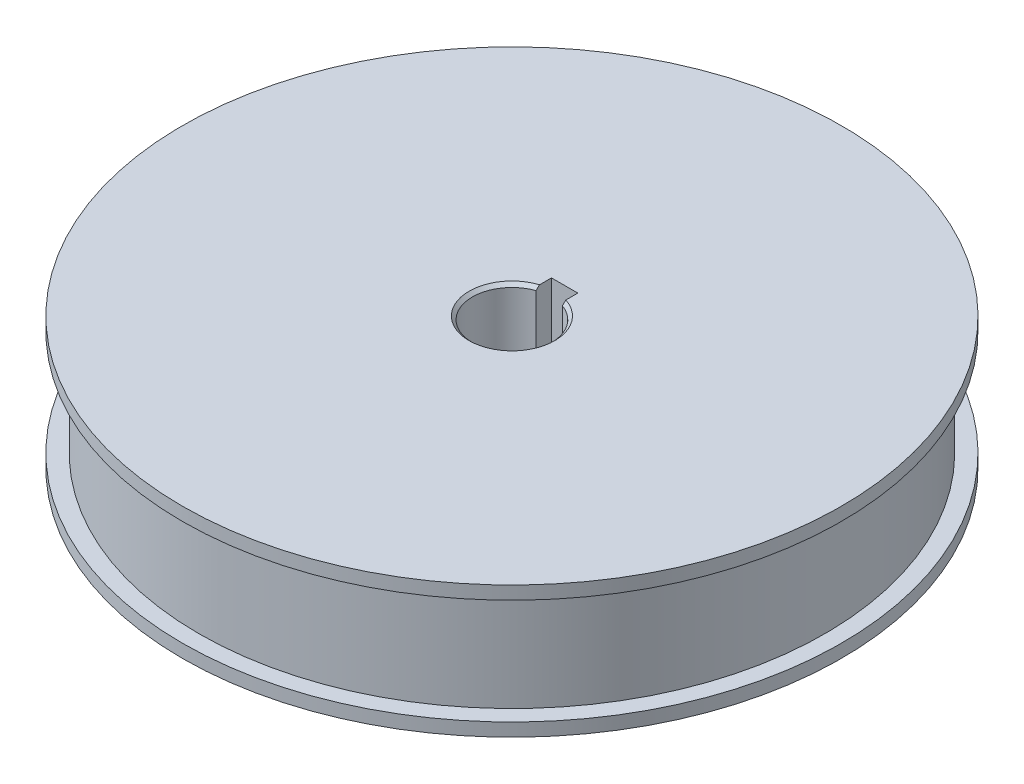
SolidWorks part; units mm, degrees
ref_plane "Front" through (0, 0, 0) normal (0, 0, 1) x (1, 0, 0)
ref_plane "Top" through (0, 0, 0) normal (0, 1, 0) x (1, 0, 0)
ref_plane "Right" through (0, 0, 0) normal (1, 0, 0) x (0, 0, -1)
sketch "草图1" plane through (0, 0, 0) normal (0, 1, 0) x (1, 0, 0)
  circle A0 centre (0, 0) radius 50
  dimension "D1" = 100
extrude "凸台-拉伸1" add sketch "草图1" along normal blind 20
sketch "草图2" plane through (0, 20, 0) normal (0, 1, 0) x (1, 0, 0)
  circle A0 centre (0, 0) radius 50
  circle A1 centre (0, 0) radius 47.5
  dimension "D1" = 95
extrude "切除-拉伸1" cut sketch "草图2" against normal blind 16 from offset 2 offset against normal yes
sketch "草图3" plane through (0, 20, 0) normal (0, 1, 0) x (1, 0, 0)
  circle A0 centre (0, 0) radius 6
  dimension "D1" = 12
extrude "切除-拉伸2" cut sketch "草图3" against normal through all
chamfer "倒角1" distance 0.5 angle 45 2 edges at (0, 0, 6) (0, 20, 6)
sketch "草图4" plane through (0, 20, 0) normal (0, 1, 0) x (1, 0, 0)
  line L1 (2, -0.343) -> (-2, -0.343)
  line L2 (2, -0.343) -> (2, 8)
  line L3 (2, 8) -> (-2, 8)
  line L4 (-2, -0.343) -> (-2, 8)
  line L5 (2, -0.343) -> (-2, 8) construction
  line L6 (2, 8) -> (-2, -0.343) construction
  point P0 (0, 3.8285)
  point P5 (0, 0)
  dimension "D1" = 4
  dimension "D2" = 8
extrude "切除-拉伸3" cut sketch "草图4" against normal through all
